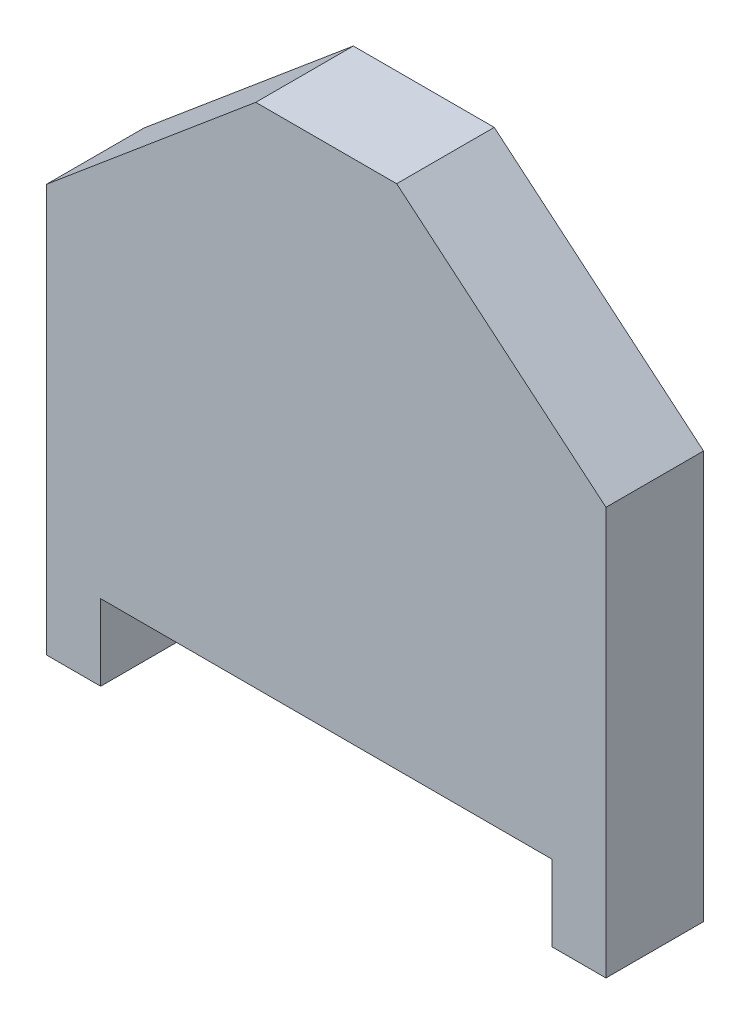
SolidWorks part; units mm, degrees
ref_plane "前视基准面" through (0, 0, 0) normal (0, 0, 1) x (1, 0, 0)
ref_plane "上视基准面" through (0, 0, 0) normal (0, 1, 0) x (1, 0, 0)
ref_plane "右视基准面" through (0, 0, 0) normal (1, 0, 0) x (0, 0, -1)
sketch "草图2" plane through (0, 0, 0) normal (0, 0, 1) x (1, 0, 0)
  line L0 (-1059.0336, -385.4567) -> (0, 0)
  line L1 (0, 0) -> (0, -470)
  line L4 (-1059.0336, -385.4567) -> (-1059.0336, -615.4567)
  line L5 (-1059.0336, -615.4567) -> (0, -470)
  line L6 (0, -390) -> (-837.1873, -524.9864)
  line L7 (-837.1873, -524.9864) -> (-837.1873, -584.9864)
  line L8 (0, 0) -> (241.304, 202.4781)
  line L9 (0, -470) -> (71, -470)
  line L10 (0, -470) -> (0, 125)
  line L12 (71, -470) -> (71, 125)
  line L13 (241.304, 202.4781) -> (241.304, -390)
  line L14 (241.304, -390) -> (0, -390)
  line L15 (241.304, 202.4781) -> (406.304, 202.4781)
  line L16 (406.304, 202.4781) -> (406.304, -390)
  line L17 (241.304, -390) -> (406.304, -390)
  line L18 (323.804, 202.4781) -> (323.804, -390) construction
  line L19 (406.304, -390) -> (647.608, -390)
  line L20 (406.304, 202.4781) -> (406.304, -390)
  line L21 (576.608, -470) -> (576.608, 125)
  line L23 (647.608, -470) -> (647.608, 125)
  line L24 (647.608, -470) -> (576.608, -470)
  line L25 (647.608, 0) -> (406.304, 202.4781)
  line L26 (1484.7953, -524.9864) -> (1484.7953, -584.9864)
  line L27 (647.608, -390) -> (1484.7953, -524.9864)
  line L28 (1706.6416, -615.4567) -> (647.608, -470)
  line L29 (1706.6416, -385.4567) -> (1706.6416, -615.4567)
  line L30 (647.608, 0) -> (647.608, -470)
  line L31 (1706.6416, -385.4567) -> (647.608, 0)
  line L32 (-206.7324, -75.2444) -> (-206.7324, -275.2444)
  line L33 (-206.7324, -275.2444) -> (-266.7324, -275.2444)
  line L34 (-266.7324, -275.2444) -> (-266.7324, 124.7556)
  line L35 (-266.7324, 124.7556) -> (-206.7324, 124.7556)
  line L36 (-206.7324, 124.7556) -> (-206.7324, -75.2444)
  line L37 (854.3404, -75.2444) -> (854.3404, -275.2444)
  line L38 (854.3404, -275.2444) -> (914.3404, -275.2444)
  line L39 (914.3404, 124.7556) -> (854.3404, 124.7556)
  line L40 (854.3404, 124.7556) -> (854.3404, -75.2444)
  line L41 (914.3404, -275.2444) -> (914.3404, 124.7556)
  line L42 (0, 125) -> (0, 175)
  line L43 (0, 175) -> (71, 175)
  line L44 (71, 175) -> (71, 125)
  line L45 (576.608, 175) -> (576.608, 125)
  line L46 (647.608, 175) -> (576.608, 175)
  line L47 (647.608, 125) -> (647.608, 175)
  line L48 (-236.7324, -275.2444) -> (-236.7324, 124.7556) construction
  line L49 (884.3404, 124.7556) -> (884.3404, -275.2444) construction
  dimension "D1" = 1127
  dimension "D2" = 470
  dimension "D3" = 230
  dimension "D4" = 0
  dimension "D5" = 70
  dimension "D6" = 0
  dimension "D7" = 80
  dimension "D8" = 60
  dimension "D9" = 848
  dimension "D10" = 71
  dimension "D11" = 595
  dimension "D12" = 130
  dimension "D13" = 315
  dimension "D14" = 165
  dimension "D15" = 220
  dimension "D16" = 200
  dimension "D17" = 200
  dimension "D18" = 60
  dimension "D19" = 50
  dimension "D20" = 1121.0728
sketch "草图3" plane through (0, 0, 0) normal (0, 0, 1) x (1, 0, 0)
  line L0 (0, -736.521) -> (0, -1112.521)
  line L1 (1258.0495, -1006.5735) -> (1258.0495, -1214.3166)
  line L2 (-741.9631, -1006.5735) -> (-741.9631, -1214.3166)
  line L3 (0, -736.521) -> (-741.9631, -1006.5735)
  line L4 (516.0864, -1042.521) -> (323.0432, -1042.521)
  line L6 (-741.9631, -1214.3166) -> (0, -1112.521)
  line L7 (703.0495, -808.5298) -> (-186.9631, -808.5298)
  line L8 (0, -1042.521) -> (-622.8268, -1147.9713)
  line L9 (-622.8268, -1147.9713) -> (-622.8268, -1197.9713)
  line L11 (0, -1112.521) -> (50, -1112.521)
  line L12 (50, -1112.521) -> (50, -596.521)
  line L14 (50, -596.521) -> (0, -596.521)
  line L15 (0, -596.521) -> (0, -736.521)
  line L16 (0, -736.521) -> (193.0432, -574.5385)
  line L17 (0, -1042.521) -> (193.0432, -1042.521)
  line L18 (193.0432, -1042.521) -> (193.0432, -574.5385)
  line L19 (193.0432, -574.5385) -> (323.0432, -574.5385)
  line L20 (323.0432, -574.5385) -> (323.0432, -1042.521)
  line L21 (323.0432, -1042.521) -> (193.0432, -1042.521)
  line L22 (258.0432, -574.5385) -> (258.0432, -1042.521) construction
  line L23 (516.0864, -736.521) -> (323.0432, -574.5385)
  line L24 (516.0864, -596.521) -> (516.0864, -736.521)
  line L25 (466.0864, -596.521) -> (516.0864, -596.521)
  line L26 (466.0864, -1112.521) -> (466.0864, -596.521)
  line L27 (516.0864, -1112.521) -> (466.0864, -1112.521)
  line L28 (1138.9132, -1147.9713) -> (1138.9132, -1197.9713)
  line L29 (516.0864, -1042.521) -> (1138.9132, -1147.9713)
  line L30 (1258.0495, -1214.3166) -> (516.0864, -1112.521)
  line L32 (516.0864, -736.521) -> (1258.0495, -1006.5735)
  line L33 (516.0864, -736.521) -> (516.0864, -1112.521)
  point P29 (258.0432, -808.5298)
  dimension "D1" = 376
  dimension "D2" = 555
  dimension "D4" = 70
  dimension "D5" = 70
  dimension "D6" = 50
  dimension "D7" = 516
  dimension "D8" = 50
  dimension "D9" = 130
  dimension "D10" = 252
  dimension "D11" = 130
sketch "草图4" plane through (0, 0, 0) normal (0, 0, 1) x (1, 0, 0)
  line L0 (323.0432, -574.5385) -> (323.0432, -1042.521) construction
  line L5 (323.0432, -1804.3792) -> (193.0432, -1804.3792)
  line L6 (323.0432, -1804.3792) -> (323.0432, -1339.3792)
  line L7 (323.0432, -1339.3792) -> (193.0432, -1339.3792)
  line L8 (193.0432, -1804.3792) -> (193.0432, -1339.3792)
  line L9 (323.0432, -1804.3792) -> (193.0432, -1339.3792) construction
  line L10 (323.0432, -1339.3792) -> (193.0432, -1804.3792) construction
  line L11 (652.1466, -2127.0447) -> (1252.1466, -2224.4809)
  line L12 (1252.1466, -2224.4809) -> (1252.1466, -2269.4809)
  line L14 (652.1466, -1797.0447) -> (652.1466, -2197.0447)
  line L15 (652.1466, -1797.0447) -> (1392.1466, -2066.3827)
  line L16 (1392.1466, -2066.3827) -> (1392.1466, -2286.3827)
  line L17 (862.1466, -1924.3792) -> (812.1466, -1924.3792)
  line L18 (1392.1466, -2286.3827) -> (652.1466, -2197.0447)
  line L19 (862.1466, -1924.3792) -> (862.1466, -1804.3792)
  line L20 (862.1466, -1804.3792) -> (812.1466, -1804.3792)
  line L21 (812.1466, -1924.3792) -> (812.1466, -1804.3792)
  line L22 (862.1466, -1924.3792) -> (812.1466, -1804.3792) construction
  line L23 (862.1466, -1804.3792) -> (812.1466, -1924.3792) construction
  point P0 (258.0432, -1571.8792)
  point P14 (837.1466, -1864.3792)
  dimension "D1" = 130
  dimension "D2" = 0
  dimension "D3" = 465
  dimension "D4" = 400
  dimension "D5" = 70
  dimension "D6" = 740
  dimension "D7" = 220
  dimension "D8" = 70
  dimension "D9" = 45
  dimension "D10" = 600
  dimension "D11" = 555
  dimension "D12" = 50
  dimension "D13" = 120
sketch "草图5" plane through (0, 0, 0) normal (0, 0, 1) x (1, 0, 0)
  line L0 (-3576.7042, -1762.1781) -> (-3696.7042, -1647.1781)
  line L1 (-3319.2042, -1945.8912) -> (-3374.2042, -1945.8912)
  line L2 (-3319.2042, -1945.8912) -> (-3319.2042, -1745.8912)
  line L3 (-3576.7042, -1762.1781) -> (-3576.7042, -2232.1781)
  line L4 (-3319.2042, -1745.8912) -> (-3374.2042, -1745.8912)
  line L6 (-3374.2042, -1945.8912) -> (-3374.2042, -1745.8912)
  line L7 (-3319.2042, -1945.8912) -> (-3374.2042, -1745.8912) construction
  line L8 (-3319.2042, -1745.8912) -> (-3374.2042, -1945.8912) construction
  line L10 (-2676.7042, -2359.7513) -> (-3576.7042, -2232.1781)
  line L11 (-3976.7042, -1762.1781) -> (-3856.7042, -1647.1781)
  line L12 (-3576.7042, -2147.1781) -> (-2846.7042, -2283.6541)
  line L13 (-2846.7042, -2283.6541) -> (-2846.7042, -2335.6541)
  line L14 (-3696.7042, -1647.1781) -> (-3856.7042, -1647.1781)
  line L16 (-2676.7042, -2359.7513) -> (-2676.7042, -2089.7513)
  line L17 (-2676.7042, -2089.7513) -> (-3576.7042, -1762.1781)
  line L20 (-3576.7042, -2147.1781) -> (-3976.7042, -2147.1781)
  line L21 (-3576.7042, -2147.1781) -> (-3576.7042, -1762.1781)
  line L23 (-3976.7042, -2147.1781) -> (-3976.7042, -1762.1781)
  line L25 (-4876.7042, -2359.7513) -> (-3976.7042, -2232.1781)
  line L26 (-3976.7042, -2147.1781) -> (-4706.7042, -2283.6541)
  line L27 (-4876.7042, -2089.7513) -> (-3976.7042, -1762.1781)
  line L28 (-4876.7042, -2359.7513) -> (-4876.7042, -2089.7513)
  line L29 (-4706.7042, -2283.6541) -> (-4706.7042, -2335.6541)
  line L30 (-3976.7042, -2147.1781) -> (-3976.7042, -2232.1781)
  line L31 (-3696.7042, -1647.1781) -> (-3696.7042, -2147.1781)
  line L32 (-3856.7042, -1647.1781) -> (-3856.7042, -2147.1781)
  point P11 (-3346.7042, -1845.8912)
  dimension "D1" = 470
  dimension "D2" = 270
  dimension "D3" = 70
  dimension "D4" = 160
  dimension "D5" = 85
  dimension "D6" = 730
  dimension "D7" = 52
  dimension "D8" = 120
  dimension "D9" = 120
  dimension "D10" = 470
  dimension "D11" = 230
  dimension "D12" = 55
  dimension "D13" = 200
  dimension "D14" = 900
  dimension "D15" = 2200
extrude "凸台-拉伸1" add sketch "草图3" along normal mid plane 90 contours L4 L26 L7 L20 | L7 L22 L21 L20 | L22 L7 L18 L21 | L17 L18 L7 L12 | L0 L17 L12 L7 | L17 L0 L11 L12 | L33 L4 L26 L27 | L33 L7 L26 L4 | L33 L23 L26 L7 | L7 L26 L23 L20 | L19 L22 L7 L20 | L22 L19 L18 L7 | L7 L18 L16 L12 | L16 L0 L7 L12
